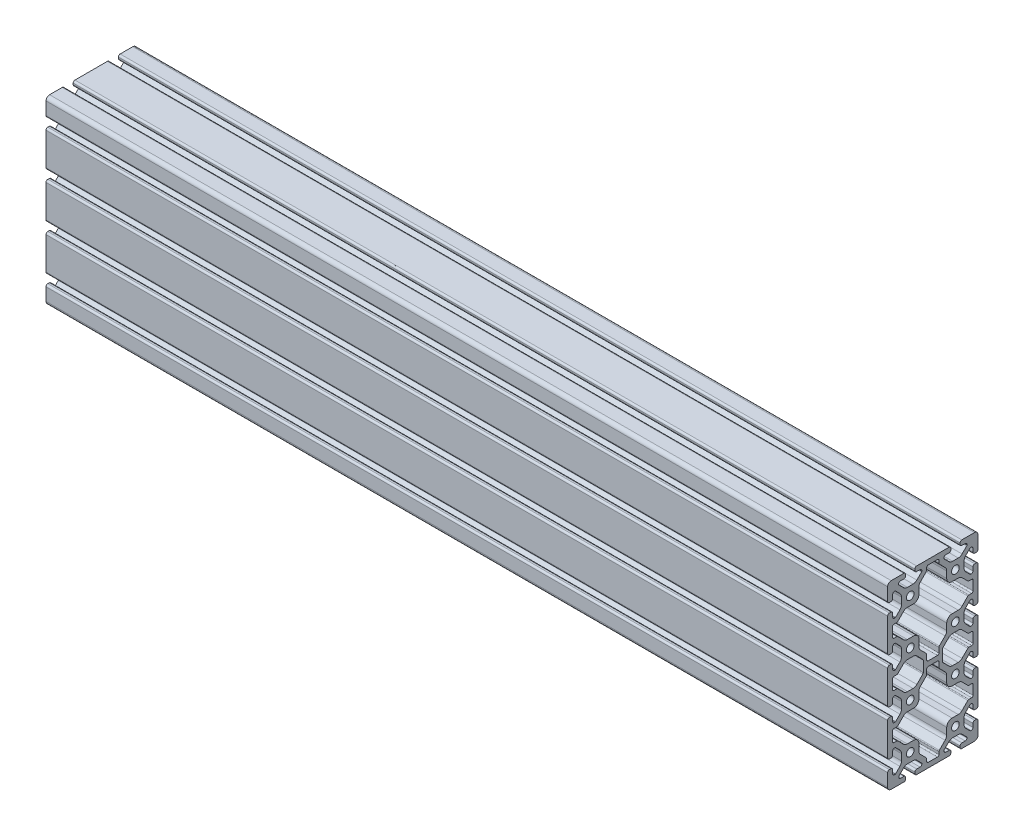
SolidWorks part; units mm, degrees
ref_plane "Front Plane" through (0, 0, 0) normal (0, 0, 1) x (1, 0, 0)
ref_plane "Top Plane" through (0, 0, 0) normal (0, 1, 0) x (1, 0, 0)
ref_plane "Right Plane" through (0, 0, 0) normal (1, 0, 0) x (0, 0, -1)
sketch "Sketch1" plane through (0, 0, 0) normal (0, 1, 0) x (1, 0, 0)
  line L0 (0, 0) -> (745, 0)
  dimension "D1" = 745
other "Aluminum 80X160(1)"
ref_plane "Plane1" through (0, 0, 0) normal (1, 0, 0) x (0, 0, -1)
sketch "Sketch13" plane through (0, 0, 0) normal (1, 0, 0) x (0, 0, -1)
  line L0 (-24.13, 57.84) -> (-15.87, 57.84)
  line L1 (-14.6, 56.57) -> (-14.6, 52.2333)
  line L2 (-14.228, 51.3353) -> (-9.1098, 46.2171)
  line L3 (-7.685, 42.7773) -> (-7.685, 37.065)
  line L4 (-2.935, 32.315) -> (2.5008, 32.315)
  line L5 (5.8595, 30.9238) -> (11.0113, 25.772)
  line L6 (11.9093, 25.4) -> (14.41, 25.4)
  line L7 (15.68, 24.13) -> (15.68, 15.87)
  line L8 (14.41, 14.6) -> (11.9093, 14.6)
  line L9 (11.0113, 14.228) -> (5.8595, 9.0762)
  line L10 (2.5008, 7.685) -> (-2.935, 7.685)
  line L11 (-7.685, 2.935) -> (-7.685, -2.7773)
  line L12 (-9.1098, -6.2171) -> (-14.228, -11.3353)
  line L13 (-14.6, -12.2334) -> (-14.6, -14.41)
  line L14 (-15.87, -15.68) -> (-24.13, -15.68)
  line L15 (-25.4, -14.41) -> (-25.4, -12.2334)
  line L16 (-25.772, -11.3353) -> (-30.8902, -6.2171)
  line L17 (-32.315, -2.7773) -> (-32.315, 2.935)
  line L18 (-37.065, 7.685) -> (-42.5008, 7.685)
  line L19 (-45.8595, 9.0762) -> (-51.0113, 14.228)
  line L20 (-51.9093, 14.6) -> (-54.41, 14.6)
  line L21 (-55.68, 15.87) -> (-55.68, 24.13)
  line L22 (-54.41, 25.4) -> (-51.9093, 25.4)
  line L23 (-51.0113, 25.772) -> (-45.8595, 30.9238)
  line L24 (-42.5008, 32.315) -> (-37.065, 32.315)
  line L25 (-32.315, 37.065) -> (-32.315, 42.7773)
  line L26 (-30.8902, 46.2171) -> (-25.772, 51.3353)
  line L27 (-25.4, 52.2333) -> (-25.4, 56.57)
  line L28 (-28.802, 54.4147) -> (-34.1405, 49.0762)
  line L29 (-37.4992, 47.685) -> (-42.5008, 47.685)
  line L30 (-45.8595, 49.0762) -> (-51.0113, 54.228)
  line L31 (-51.9093, 54.6) -> (-54.41, 54.6)
  line L32 (-55.68, 55.87) -> (-55.68, 64.13)
  line L33 (-54.41, 65.4) -> (-51.9093, 65.4)
  line L34 (-51.0113, 65.772) -> (-45.8595, 70.9238)
  line L35 (-42.5008, 72.315) -> (-37.4992, 72.315)
  line L36 (-34.1405, 70.9238) -> (-28.802, 65.5853)
  line L37 (-28.43, 64.6872) -> (-28.43, 55.3128)
  line L38 (-11.57, 55.3128) -> (-11.57, 64.6872)
  line L39 (-11.198, 65.5853) -> (-5.8595, 70.9238)
  line L40 (-2.5008, 72.315) -> (2.5008, 72.315)
  line L41 (5.8595, 70.9238) -> (11.0113, 65.772)
  line L42 (11.9093, 65.4) -> (14.41, 65.4)
  line L43 (15.68, 64.13) -> (15.68, 55.87)
  line L44 (14.41, 54.6) -> (11.9093, 54.6)
  line L45 (11.0113, 54.228) -> (5.8595, 49.0762)
  line L46 (2.5008, 47.685) -> (-2.5008, 47.685)
  line L47 (-5.8595, 49.0762) -> (-11.198, 54.4147)
  line L48 (-15.87, 62.16) -> (-24.13, 62.16)
  line L49 (-25.4, 63.43) -> (-25.4, 67.7667)
  line L50 (-25.772, 68.6647) -> (-30.8902, 73.7829)
  line L51 (-32.315, 77.2227) -> (-32.315, 82.935)
  line L52 (-37.065, 87.685) -> (-42.5008, 87.685)
  line L53 (-45.8595, 89.0762) -> (-51.0113, 94.228)
  line L54 (-51.9093, 94.6) -> (-54.41, 94.6)
  line L55 (-55.68, 95.87) -> (-55.68, 104.13)
  line L56 (-54.41, 105.4) -> (-51.9093, 105.4)
  line L57 (-51.0113, 105.772) -> (-45.8595, 110.9238)
  line L58 (-42.5008, 112.315) -> (-37.065, 112.315)
  line L59 (-32.315, 117.065) -> (-32.315, 122.7773)
  line L60 (-30.8902, 126.2171) -> (-25.772, 131.3353)
  line L61 (-25.4, 132.2334) -> (-25.4, 134.41)
  line L62 (-24.13, 135.68) -> (-15.87, 135.68)
  line L63 (-14.6, 134.41) -> (-14.6, 132.2334)
  line L64 (-14.228, 131.3353) -> (-9.1098, 126.2171)
  line L65 (-7.685, 122.7773) -> (-7.685, 117.065)
  line L66 (-2.935, 112.315) -> (2.5008, 112.315)
  line L67 (5.8595, 110.9238) -> (11.0113, 105.772)
  line L68 (11.9093, 105.4) -> (14.41, 105.4)
  line L69 (15.68, 104.13) -> (15.68, 95.87)
  line L70 (14.41, 94.6) -> (11.9093, 94.6)
  line L71 (11.0113, 94.228) -> (5.8595, 89.0762)
  line L72 (2.5008, 87.685) -> (-2.935, 87.685)
  line L73 (-7.685, 82.935) -> (-7.685, 77.2227)
  line L74 (-9.1098, 73.7829) -> (-14.228, 68.6647)
  line L75 (-14.6, 67.7667) -> (-14.6, 63.43)
  line L76 (18.43, 115.94) -> (17.0946, 115.94)
  line L77 (15.5246, 114.37) -> (15.5246, 111.285)
  line L78 (13.9546, 109.715) -> (13.4925, 109.715)
  line L79 (12.9551, 109.9376) -> (9.1098, 113.7829)
  line L80 (7.685, 117.2227) -> (7.685, 122.7773)
  line L81 (9.1098, 126.2171) -> (12.9551, 130.0624)
  line L82 (13.4925, 130.285) -> (13.9546, 130.285)
  line L83 (15.5246, 128.715) -> (15.5246, 125.63)
  line L84 (17.0946, 124.06) -> (18.43, 124.06)
  line L85 (20, 125.63) -> (20, 136.83)
  line L86 (16.83, 140) -> (5.63, 140)
  line L87 (4.06, 138.43) -> (4.06, 137.25)
  line L88 (5.63, 135.68) -> (8.7154, 135.68)
  line L89 (10.2854, 134.11) -> (10.2854, 133.6201)
  line L90 (9.947, 133.1637) -> (5.8595, 129.0762)
  line L91 (2.5008, 127.685) -> (-2.5008, 127.685)
  line L92 (-5.8595, 129.0762) -> (-10.0628, 133.2795)
  line L93 (-10.2854, 133.8169) -> (-10.2854, 134.11)
  line L94 (-8.7154, 135.68) -> (-5.63, 135.68)
  line L95 (-4.06, 137.25) -> (-4.06, 138.43)
  line L96 (-5.63, 140) -> (-34.37, 140)
  line L97 (-35.94, 138.43) -> (-35.94, 137.25)
  line L98 (-34.37, 135.68) -> (-31.2846, 135.68)
  line L99 (-29.7146, 134.11) -> (-29.7146, 133.6201)
  line L100 (-30.053, 133.1637) -> (-34.1405, 129.0762)
  line L101 (-37.4992, 127.685) -> (-42.5008, 127.685)
  line L102 (-45.8595, 129.0762) -> (-50.0628, 133.2795)
  line L103 (-50.2854, 133.8169) -> (-50.2854, 134.11)
  line L104 (-48.7154, 135.68) -> (-45.63, 135.68)
  line L105 (-44.06, 137.25) -> (-44.06, 138.43)
  line L106 (-45.63, 140) -> (-56.83, 140)
  line L107 (-60, 136.83) -> (-60, 125.63)
  line L108 (-58.43, 124.06) -> (-57.0946, 124.06)
  line L109 (-55.5246, 125.63) -> (-55.5246, 128.715)
  line L110 (-53.9546, 130.285) -> (-53.4925, 130.285)
  line L111 (-52.9551, 130.0624) -> (-49.1098, 126.2171)
  line L112 (-47.685, 122.7773) -> (-47.685, 117.2227)
  line L113 (-49.1098, 113.7829) -> (-52.9551, 109.9376)
  line L114 (-53.4925, 109.715) -> (-53.9546, 109.715)
  line L115 (-55.5246, 111.285) -> (-55.5246, 114.37)
  line L116 (-57.0946, 115.94) -> (-58.43, 115.94)
  line L117 (-60, 114.37) -> (-60, 85.63)
  line L118 (-58.43, 84.06) -> (-57.0946, 84.06)
  line L119 (-55.5246, 85.63) -> (-55.5246, 88.715)
  line L120 (-53.9546, 90.285) -> (-53.4925, 90.285)
  line L121 (-52.9551, 90.0624) -> (-49.1098, 86.2171)
  line L122 (-47.685, 82.7773) -> (-47.685, 77.2227)
  line L123 (-49.1098, 73.7829) -> (-52.9551, 69.9376)
  line L124 (-53.4925, 69.715) -> (-53.9546, 69.715)
  line L125 (-55.5246, 71.285) -> (-55.5246, 74.37)
  line L126 (-57.0946, 75.94) -> (-58.43, 75.94)
  line L127 (-60, 74.37) -> (-60, 45.63)
  line L128 (-58.43, 44.06) -> (-57.0946, 44.06)
  line L129 (-55.5246, 45.63) -> (-55.5246, 48.715)
  line L130 (-53.9546, 50.285) -> (-53.4925, 50.285)
  line L131 (-52.9551, 50.0624) -> (-49.1098, 46.2171)
  line L132 (-47.685, 42.7773) -> (-47.685, 37.2227)
  line L133 (-49.1098, 33.7829) -> (-52.9551, 29.9376)
  line L134 (-53.4925, 29.715) -> (-53.9546, 29.715)
  line L135 (-55.5246, 31.285) -> (-55.5246, 34.37)
  line L136 (-57.0946, 35.94) -> (-58.43, 35.94)
  line L137 (-60, 34.37) -> (-60, 5.63)
  line L138 (-58.43, 4.06) -> (-57.0946, 4.06)
  line L139 (-55.5246, 5.63) -> (-55.5246, 8.715)
  line L140 (-53.9546, 10.285) -> (-53.4925, 10.285)
  line L141 (-52.9551, 10.0624) -> (-49.1098, 6.2171)
  line L142 (-47.685, 2.7773) -> (-47.685, -2.7773)
  line L143 (-49.1098, -6.2171) -> (-52.9551, -10.0624)
  line L144 (-53.4925, -10.285) -> (-53.9546, -10.285)
  line L145 (-55.5246, -8.715) -> (-55.5246, -5.63)
  line L146 (-57.0946, -4.06) -> (-58.43, -4.06)
  line L147 (-60, -5.63) -> (-60, -16.83)
  line L148 (-56.83, -20) -> (-45.573, -20)
  line L149 (-44.003, -18.43) -> (-44.003, -17.25)
  line L150 (-45.573, -15.68) -> (-48.4757, -15.68)
  line L151 (-50.0447, -14.0552) -> (-50.033, -13.7199)
  line L152 (-49.8238, -13.0405) -> (-45.8595, -9.0762)
  line L153 (-42.5008, -7.685) -> (-37.4992, -7.685)
  line L154 (-34.1405, -9.0762) -> (-29.9372, -13.2795)
  line L155 (-29.7146, -13.8169) -> (-29.7146, -14.11)
  line L156 (-31.2846, -15.68) -> (-34.2421, -15.68)
  line L157 (-35.8795, -17.25) -> (-35.8795, -18.43)
  line L158 (-34.2421, -20) -> (-5.573, -20)
  line L159 (-4.003, -18.43) -> (-4.003, -17.25)
  line L160 (-5.573, -15.68) -> (-8.4757, -15.68)
  line L161 (-10.0447, -14.0552) -> (-10.033, -13.7199)
  line L162 (-9.8238, -13.0405) -> (-5.8595, -9.0762)
  line L163 (-2.5008, -7.685) -> (2.5008, -7.685)
  line L164 (5.8595, -9.0762) -> (10.0628, -13.2795)
  line L165 (10.2854, -13.8169) -> (10.2854, -14.11)
  line L166 (8.7154, -15.68) -> (5.7579, -15.68)
  line L167 (4.1204, -17.2515) -> (4.1204, -18.4315)
  line L168 (5.7579, -20) -> (17.0184, -20)
  line L169 (20, -16.6746) -> (20, -5.63)
  line L170 (18.43, -4.06) -> (17.0946, -4.06)
  line L171 (15.5246, -5.63) -> (15.5246, -8.715)
  line L172 (13.9546, -10.285) -> (13.4925, -10.285)
  line L173 (12.9551, -10.0624) -> (9.1098, -6.2171)
  line L174 (7.685, -2.7773) -> (7.685, 2.7773)
  line L175 (9.1098, 6.2171) -> (12.9551, 10.0624)
  line L176 (13.4925, 10.285) -> (13.9546, 10.285)
  line L177 (15.5246, 8.715) -> (15.5246, 5.63)
  line L178 (17.0946, 4.06) -> (18.43, 4.06)
  line L179 (20, 5.63) -> (20, 34.37)
  line L180 (18.43, 35.94) -> (17.0946, 35.94)
  line L181 (15.5246, 34.37) -> (15.5246, 31.285)
  line L182 (13.9546, 29.715) -> (13.4925, 29.715)
  line L183 (12.9551, 29.9376) -> (9.1098, 33.7829)
  line L184 (7.685, 37.2227) -> (7.685, 42.7773)
  line L185 (9.1098, 46.2171) -> (12.9551, 50.0624)
  line L186 (13.4925, 50.285) -> (13.9546, 50.285)
  line L187 (15.5246, 48.715) -> (15.5246, 45.63)
  line L188 (17.0946, 44.06) -> (18.43, 44.06)
  line L189 (20, 45.63) -> (20, 74.37)
  line L190 (18.43, 75.94) -> (17.0946, 75.94)
  line L191 (15.5246, 74.37) -> (15.5246, 71.285)
  line L192 (13.9546, 69.715) -> (13.4925, 69.715)
  line L193 (12.9551, 69.9376) -> (9.1098, 73.7829)
  line L194 (7.685, 77.2227) -> (7.685, 82.7773)
  line L195 (9.1098, 86.2171) -> (12.9551, 90.0624)
  line L196 (13.4925, 90.285) -> (13.9546, 90.285)
  line L197 (15.5246, 88.715) -> (15.5246, 85.63)
  line L198 (17.0946, 84.06) -> (18.43, 84.06)
  line L199 (20, 85.63) -> (20, 114.37)
  arc A0 (-14.6, 56.57) -> (-15.87, 57.84) centre (-15.87, 56.57) ccw
  arc A1 (-14.6, 52.2333) -> (-14.228, 51.3353) centre (-13.33, 52.2333) ccw
  arc A2 (-7.685, 42.7773) -> (-9.1098, 46.2171) centre (-12.5496, 42.7773) ccw
  arc A3 (-7.685, 37.065) -> (-2.935, 32.315) centre (-2.935, 37.065) ccw
  arc A4 (5.8595, 30.9238) -> (2.5008, 32.315) centre (2.5008, 27.565) ccw
  arc A5 (11.0113, 25.772) -> (11.9093, 25.4) centre (11.9093, 26.67) ccw
  arc A6 (15.68, 24.13) -> (14.41, 25.4) centre (14.41, 24.13) ccw
  arc A7 (14.41, 14.6) -> (15.68, 15.87) centre (14.41, 15.87) ccw
  arc A8 (11.9093, 14.6) -> (11.0113, 14.228) centre (11.9093, 13.33) ccw
  arc A9 (2.5008, 7.685) -> (5.8595, 9.0762) centre (2.5008, 12.435) ccw
  arc A10 (-2.935, 7.685) -> (-7.685, 2.935) centre (-2.935, 2.935) ccw
  arc A11 (-9.1098, -6.2171) -> (-7.685, -2.7773) centre (-12.5496, -2.7773) ccw
  arc A12 (-14.228, -11.3353) -> (-14.6, -12.2334) centre (-13.33, -12.2334) ccw
  arc A13 (-15.87, -15.68) -> (-14.6, -14.41) centre (-15.87, -14.41) ccw
  arc A14 (-25.4, -14.41) -> (-24.13, -15.68) centre (-24.13, -14.41) ccw
  arc A15 (-25.4, -12.2334) -> (-25.772, -11.3353) centre (-26.67, -12.2334) ccw
  arc A16 (-32.315, -2.7773) -> (-30.8902, -6.2171) centre (-27.4504, -2.7773) ccw
  arc A17 (-32.315, 2.935) -> (-37.065, 7.685) centre (-37.065, 2.935) ccw
  arc A18 (-45.8595, 9.0762) -> (-42.5008, 7.685) centre (-42.5008, 12.435) ccw
  arc A19 (-51.0113, 14.228) -> (-51.9093, 14.6) centre (-51.9093, 13.33) ccw
  arc A20 (-55.68, 15.87) -> (-54.41, 14.6) centre (-54.41, 15.87) ccw
  arc A21 (-54.41, 25.4) -> (-55.68, 24.13) centre (-54.41, 24.13) ccw
  arc A22 (-51.9093, 25.4) -> (-51.0113, 25.772) centre (-51.9093, 26.67) ccw
  arc A23 (-42.5008, 32.315) -> (-45.8595, 30.9238) centre (-42.5008, 27.565) ccw
  arc A24 (-37.065, 32.315) -> (-32.315, 37.065) centre (-37.065, 37.065) ccw
  arc A25 (-30.8902, 46.2171) -> (-32.315, 42.7773) centre (-27.4504, 42.7773) ccw
  arc A26 (-25.772, 51.3353) -> (-25.4, 52.2333) centre (-26.67, 52.2333) ccw
  arc A27 (-24.13, 57.84) -> (-25.4, 56.57) centre (-24.13, 56.57) ccw
  arc A28 (-28.802, 54.4147) -> (-28.43, 55.3128) centre (-29.7, 55.3128) ccw
  arc A29 (-37.4992, 47.685) -> (-34.1405, 49.0762) centre (-37.4992, 52.435) ccw
  arc A30 (-45.8595, 49.0762) -> (-42.5008, 47.685) centre (-42.5008, 52.435) ccw
  arc A31 (-51.0113, 54.228) -> (-51.9093, 54.6) centre (-51.9093, 53.33) ccw
  arc A32 (-55.68, 55.87) -> (-54.41, 54.6) centre (-54.41, 55.87) ccw
  arc A33 (-54.41, 65.4) -> (-55.68, 64.13) centre (-54.41, 64.13) ccw
  arc A34 (-51.9093, 65.4) -> (-51.0113, 65.772) centre (-51.9093, 66.67) ccw
  arc A35 (-42.5008, 72.315) -> (-45.8595, 70.9238) centre (-42.5008, 67.565) ccw
  arc A36 (-34.1405, 70.9238) -> (-37.4992, 72.315) centre (-37.4992, 67.565) ccw
  arc A37 (-28.43, 64.6872) -> (-28.802, 65.5853) centre (-29.7, 64.6872) ccw
  circle A38 centre (-40, 40) radius 3.4
  circle A39 centre (0, 40) radius 3.4
  circle A40 centre (-40, 120) radius 3.4
  circle A41 centre (0, 120) radius 3.4
  circle A42 centre (0, 80) radius 3.4
  circle A43 centre (-40, 80) radius 3.4
  circle A44 centre (0, 0) radius 3.4
  circle A45 centre (-40, 0) radius 3.4
  arc A46 (-11.198, 65.5853) -> (-11.57, 64.6872) centre (-10.3, 64.6872) ccw
  arc A47 (-2.5008, 72.315) -> (-5.8595, 70.9238) centre (-2.5008, 67.565) ccw
  arc A48 (5.8595, 70.9238) -> (2.5008, 72.315) centre (2.5008, 67.565) ccw
  arc A49 (11.0113, 65.772) -> (11.9093, 65.4) centre (11.9093, 66.67) ccw
  arc A50 (15.68, 64.13) -> (14.41, 65.4) centre (14.41, 64.13) ccw
  arc A51 (14.41, 54.6) -> (15.68, 55.87) centre (14.41, 55.87) ccw
  arc A52 (11.9093, 54.6) -> (11.0113, 54.228) centre (11.9093, 53.33) ccw
  arc A53 (2.5008, 47.685) -> (5.8595, 49.0762) centre (2.5008, 52.435) ccw
  arc A54 (-5.8595, 49.0762) -> (-2.5008, 47.685) centre (-2.5008, 52.435) ccw
  arc A55 (-11.57, 55.3128) -> (-11.198, 54.4147) centre (-10.3, 55.3128) ccw
  arc A56 (-15.87, 62.16) -> (-14.6, 63.43) centre (-15.87, 63.43) ccw
  arc A57 (-25.4, 63.43) -> (-24.13, 62.16) centre (-24.13, 63.43) ccw
  arc A58 (-25.4, 67.7667) -> (-25.772, 68.6647) centre (-26.67, 67.7667) ccw
  arc A59 (-32.315, 77.2227) -> (-30.8902, 73.7829) centre (-27.4504, 77.2227) ccw
  arc A60 (-32.315, 82.935) -> (-37.065, 87.685) centre (-37.065, 82.935) ccw
  arc A61 (-45.8595, 89.0762) -> (-42.5008, 87.685) centre (-42.5008, 92.435) ccw
  arc A62 (-51.0113, 94.228) -> (-51.9093, 94.6) centre (-51.9093, 93.33) ccw
  arc A63 (-55.68, 95.87) -> (-54.41, 94.6) centre (-54.41, 95.87) ccw
  arc A64 (-54.41, 105.4) -> (-55.68, 104.13) centre (-54.41, 104.13) ccw
  arc A65 (-51.9093, 105.4) -> (-51.0113, 105.772) centre (-51.9093, 106.67) ccw
  arc A66 (-42.5008, 112.315) -> (-45.8595, 110.9238) centre (-42.5008, 107.565) ccw
  arc A67 (-37.065, 112.315) -> (-32.315, 117.065) centre (-37.065, 117.065) ccw
  arc A68 (-30.8902, 126.2171) -> (-32.315, 122.7773) centre (-27.4504, 122.7773) ccw
  arc A69 (-25.772, 131.3353) -> (-25.4, 132.2334) centre (-26.67, 132.2334) ccw
  arc A70 (-24.13, 135.68) -> (-25.4, 134.41) centre (-24.13, 134.41) ccw
  arc A71 (-14.6, 134.41) -> (-15.87, 135.68) centre (-15.87, 134.41) ccw
  arc A72 (-14.6, 132.2334) -> (-14.228, 131.3353) centre (-13.33, 132.2334) ccw
  arc A73 (-7.685, 122.7773) -> (-9.1098, 126.2171) centre (-12.5496, 122.7773) ccw
  arc A74 (-7.685, 117.065) -> (-2.935, 112.315) centre (-2.935, 117.065) ccw
  arc A75 (5.8595, 110.9238) -> (2.5008, 112.315) centre (2.5008, 107.565) ccw
  arc A76 (11.0113, 105.772) -> (11.9093, 105.4) centre (11.9093, 106.67) ccw
  arc A77 (15.68, 104.13) -> (14.41, 105.4) centre (14.41, 104.13) ccw
  arc A78 (14.41, 94.6) -> (15.68, 95.87) centre (14.41, 95.87) ccw
  arc A79 (11.9093, 94.6) -> (11.0113, 94.228) centre (11.9093, 93.33) ccw
  arc A80 (2.5008, 87.685) -> (5.8595, 89.0762) centre (2.5008, 92.435) ccw
  arc A81 (-2.935, 87.685) -> (-7.685, 82.935) centre (-2.935, 82.935) ccw
  arc A82 (-9.1098, 73.7829) -> (-7.685, 77.2227) centre (-12.5496, 77.2227) ccw
  arc A83 (-14.228, 68.6647) -> (-14.6, 67.7667) centre (-13.33, 67.7667) ccw
  arc A84 (17.0946, 115.94) -> (15.5246, 114.37) centre (17.0946, 114.37) ccw
  arc A85 (13.9546, 109.715) -> (15.5246, 111.285) centre (13.9546, 111.285) ccw
  arc A86 (12.9551, 109.9376) -> (13.4925, 109.715) centre (13.4925, 110.475) ccw
  arc A87 (7.685, 117.2227) -> (9.1098, 113.7829) centre (12.5496, 117.2227) ccw
  arc A88 (9.1098, 126.2171) -> (7.685, 122.7773) centre (12.5496, 122.7773) ccw
  arc A89 (13.4925, 130.285) -> (12.9551, 130.0624) centre (13.4925, 129.525) ccw
  arc A90 (15.5246, 128.715) -> (13.9546, 130.285) centre (13.9546, 128.715) ccw
  arc A91 (15.5246, 125.63) -> (17.0946, 124.06) centre (17.0946, 125.63) ccw
  arc A92 (18.43, 124.06) -> (20, 125.63) centre (18.43, 125.63) ccw
  arc A93 (20, 136.83) -> (16.83, 140) centre (16.83, 136.83) ccw
  arc A94 (5.63, 140) -> (4.06, 138.43) centre (5.63, 138.43) ccw
  arc A95 (4.06, 137.25) -> (5.63, 135.68) centre (5.63, 137.25) ccw
  arc A96 (10.2854, 134.11) -> (8.7154, 135.68) centre (8.7154, 134.11) ccw
  arc A97 (9.947, 133.1637) -> (10.2854, 133.6201) centre (9.55, 133.8117) ccw
  arc A98 (2.5008, 127.685) -> (5.8595, 129.0762) centre (2.5008, 132.435) ccw
  arc A99 (-5.8595, 129.0762) -> (-2.5008, 127.685) centre (-2.5008, 132.435) ccw
  arc A100 (-10.2854, 133.8169) -> (-10.0628, 133.2795) centre (-9.5254, 133.8169) ccw
  arc A101 (-8.7154, 135.68) -> (-10.2854, 134.11) centre (-8.7154, 134.11) ccw
  arc A102 (-5.63, 135.68) -> (-4.06, 137.25) centre (-5.63, 137.25) ccw
  arc A103 (-4.06, 138.43) -> (-5.63, 140) centre (-5.63, 138.43) ccw
  arc A104 (-34.37, 140) -> (-35.94, 138.43) centre (-34.37, 138.43) ccw
  arc A105 (-35.94, 137.25) -> (-34.37, 135.68) centre (-34.37, 137.25) ccw
  arc A106 (-29.7146, 134.11) -> (-31.2846, 135.68) centre (-31.2846, 134.11) ccw
  arc A107 (-30.053, 133.1637) -> (-29.7146, 133.6201) centre (-30.45, 133.8117) ccw
  arc A108 (-37.4992, 127.685) -> (-34.1405, 129.0762) centre (-37.4992, 132.435) ccw
  arc A109 (-45.8595, 129.0762) -> (-42.5008, 127.685) centre (-42.5008, 132.435) ccw
  arc A110 (-50.2854, 133.8169) -> (-50.0628, 133.2795) centre (-49.5254, 133.8169) ccw
  arc A111 (-48.7154, 135.68) -> (-50.2854, 134.11) centre (-48.7154, 134.11) ccw
  arc A112 (-45.63, 135.68) -> (-44.06, 137.25) centre (-45.63, 137.25) ccw
  arc A113 (-44.06, 138.43) -> (-45.63, 140) centre (-45.63, 138.43) ccw
  arc A114 (-56.83, 140) -> (-60, 136.83) centre (-56.83, 136.83) ccw
  arc A115 (-60, 125.63) -> (-58.43, 124.06) centre (-58.43, 125.63) ccw
  arc A116 (-57.0946, 124.06) -> (-55.5246, 125.63) centre (-57.0946, 125.63) ccw
  arc A117 (-53.9546, 130.285) -> (-55.5246, 128.715) centre (-53.9546, 128.715) ccw
  arc A118 (-52.9551, 130.0624) -> (-53.4925, 130.285) centre (-53.4925, 129.525) ccw
  arc A119 (-47.685, 122.7773) -> (-49.1098, 126.2171) centre (-52.5496, 122.7773) ccw
  arc A120 (-49.1098, 113.7829) -> (-47.685, 117.2227) centre (-52.5496, 117.2227) ccw
  arc A121 (-53.4925, 109.715) -> (-52.9551, 109.9376) centre (-53.4925, 110.475) ccw
  arc A122 (-55.5246, 111.285) -> (-53.9546, 109.715) centre (-53.9546, 111.285) ccw
  arc A123 (-55.5246, 114.37) -> (-57.0946, 115.94) centre (-57.0946, 114.37) ccw
  arc A124 (-58.43, 115.94) -> (-60, 114.37) centre (-58.43, 114.37) ccw
  arc A125 (-60, 85.63) -> (-58.43, 84.06) centre (-58.43, 85.63) ccw
  arc A126 (-57.0946, 84.06) -> (-55.5246, 85.63) centre (-57.0946, 85.63) ccw
  arc A127 (-53.9546, 90.285) -> (-55.5246, 88.715) centre (-53.9546, 88.715) ccw
  arc A128 (-52.9551, 90.0624) -> (-53.4925, 90.285) centre (-53.4925, 89.525) ccw
  arc A129 (-47.685, 82.7773) -> (-49.1098, 86.2171) centre (-52.5496, 82.7773) ccw
  arc A130 (-49.1098, 73.7829) -> (-47.685, 77.2227) centre (-52.5496, 77.2227) ccw
  arc A131 (-53.4925, 69.715) -> (-52.9551, 69.9376) centre (-53.4925, 70.475) ccw
  arc A132 (-55.5246, 71.285) -> (-53.9546, 69.715) centre (-53.9546, 71.285) ccw
  arc A133 (-55.5246, 74.37) -> (-57.0946, 75.94) centre (-57.0946, 74.37) ccw
  arc A134 (-58.43, 75.94) -> (-60, 74.37) centre (-58.43, 74.37) ccw
  arc A135 (-60, 45.63) -> (-58.43, 44.06) centre (-58.43, 45.63) ccw
  arc A136 (-57.0946, 44.06) -> (-55.5246, 45.63) centre (-57.0946, 45.63) ccw
  arc A137 (-53.9546, 50.285) -> (-55.5246, 48.715) centre (-53.9546, 48.715) ccw
  arc A138 (-52.9551, 50.0624) -> (-53.4925, 50.285) centre (-53.4925, 49.525) ccw
  arc A139 (-47.685, 42.7773) -> (-49.1098, 46.2171) centre (-52.5496, 42.7773) ccw
  arc A140 (-49.1098, 33.7829) -> (-47.685, 37.2227) centre (-52.5496, 37.2227) ccw
  arc A141 (-53.4925, 29.715) -> (-52.9551, 29.9376) centre (-53.4925, 30.475) ccw
  arc A142 (-55.5246, 31.285) -> (-53.9546, 29.715) centre (-53.9546, 31.285) ccw
  arc A143 (-55.5246, 34.37) -> (-57.0946, 35.94) centre (-57.0946, 34.37) ccw
  arc A144 (-58.43, 35.94) -> (-60, 34.37) centre (-58.43, 34.37) ccw
  arc A145 (-60, 5.63) -> (-58.43, 4.06) centre (-58.43, 5.63) ccw
  arc A146 (-57.0946, 4.06) -> (-55.5246, 5.63) centre (-57.0946, 5.63) ccw
  arc A147 (-53.9546, 10.285) -> (-55.5246, 8.715) centre (-53.9546, 8.715) ccw
  arc A148 (-52.9551, 10.0624) -> (-53.4925, 10.285) centre (-53.4925, 9.525) ccw
  arc A149 (-47.685, 2.7773) -> (-49.1098, 6.2171) centre (-52.5496, 2.7773) ccw
  arc A150 (-49.1098, -6.2171) -> (-47.685, -2.7773) centre (-52.5496, -2.7773) ccw
  arc A151 (-53.4925, -10.285) -> (-52.9551, -10.0624) centre (-53.4925, -9.525) ccw
  arc A152 (-55.5246, -8.715) -> (-53.9546, -10.285) centre (-53.9546, -8.715) ccw
  arc A153 (-55.5246, -5.63) -> (-57.0946, -4.06) centre (-57.0946, -5.63) ccw
  arc A154 (-58.43, -4.06) -> (-60, -5.63) centre (-58.43, -5.63) ccw
  arc A155 (-60, -16.83) -> (-56.83, -20) centre (-56.83, -16.83) ccw
  arc A156 (-45.573, -20) -> (-44.003, -18.43) centre (-45.573, -18.43) ccw
  arc A157 (-44.003, -17.25) -> (-45.573, -15.68) centre (-45.573, -17.25) ccw
  arc A158 (-50.0447, -14.0552) -> (-48.4757, -15.68) centre (-48.4757, -14.11) ccw
  arc A159 (-49.8238, -13.0405) -> (-50.033, -13.7199) centre (-49.2864, -13.5779) ccw
  arc A160 (-42.5008, -7.685) -> (-45.8595, -9.0762) centre (-42.5008, -12.435) ccw
  arc A161 (-34.1405, -9.0762) -> (-37.4992, -7.685) centre (-37.4992, -12.435) ccw
  arc A162 (-29.7146, -13.8169) -> (-29.9372, -13.2795) centre (-30.4746, -13.8169) ccw
  arc A163 (-31.2846, -15.68) -> (-29.7146, -14.11) centre (-31.2846, -14.11) ccw
  arc A164 (-34.2421, -15.68) -> (-35.8795, -17.25) centre (-34.3096, -17.2485) ccw
  arc A165 (-35.8795, -18.43) -> (-34.2421, -20) centre (-34.3096, -18.4315) ccw
  arc A166 (-5.573, -20) -> (-4.003, -18.43) centre (-5.573, -18.43) ccw
  arc A167 (-4.003, -17.25) -> (-5.573, -15.68) centre (-5.573, -17.25) ccw
  arc A168 (-10.0447, -14.0552) -> (-8.4757, -15.68) centre (-8.4757, -14.11) ccw
  arc A169 (-9.8238, -13.0405) -> (-10.033, -13.7199) centre (-9.2864, -13.5779) ccw
  arc A170 (-2.5008, -7.685) -> (-5.8595, -9.0762) centre (-2.5008, -12.435) ccw
  arc A171 (5.8595, -9.0762) -> (2.5008, -7.685) centre (2.5008, -12.435) ccw
  arc A172 (10.2854, -13.8169) -> (10.0628, -13.2795) centre (9.5254, -13.8169) ccw
  arc A173 (8.7154, -15.68) -> (10.2854, -14.11) centre (8.7154, -14.11) ccw
  arc A174 (5.7579, -15.68) -> (4.1204, -17.2515) centre (5.6932, -17.2515) ccw
  arc A175 (4.1204, -18.4315) -> (5.7579, -20) centre (5.6904, -18.4315) ccw
  arc A176 (17.0184, -20) -> (20, -16.6746) centre (16.8341, -16.8354) ccw
  arc A177 (20, -5.63) -> (18.43, -4.06) centre (18.43, -5.63) ccw
  arc A178 (17.0946, -4.06) -> (15.5246, -5.63) centre (17.0946, -5.63) ccw
  arc A179 (13.9546, -10.285) -> (15.5246, -8.715) centre (13.9546, -8.715) ccw
  arc A180 (12.9551, -10.0624) -> (13.4925, -10.285) centre (13.4925, -9.525) ccw
  arc A181 (7.685, -2.7773) -> (9.1098, -6.2171) centre (12.5496, -2.7773) ccw
  arc A182 (9.1098, 6.2171) -> (7.685, 2.7773) centre (12.5496, 2.7773) ccw
  arc A183 (13.4925, 10.285) -> (12.9551, 10.0624) centre (13.4925, 9.525) ccw
  arc A184 (15.5246, 8.715) -> (13.9546, 10.285) centre (13.9546, 8.715) ccw
  arc A185 (15.5246, 5.63) -> (17.0946, 4.06) centre (17.0946, 5.63) ccw
  arc A186 (18.43, 4.06) -> (20, 5.63) centre (18.43, 5.63) ccw
  arc A187 (20, 34.37) -> (18.43, 35.94) centre (18.43, 34.37) ccw
  arc A188 (17.0946, 35.94) -> (15.5246, 34.37) centre (17.0946, 34.37) ccw
  arc A189 (13.9546, 29.715) -> (15.5246, 31.285) centre (13.9546, 31.285) ccw
  arc A190 (12.9551, 29.9376) -> (13.4925, 29.715) centre (13.4925, 30.475) ccw
  arc A191 (7.685, 37.2227) -> (9.1098, 33.7829) centre (12.5496, 37.2227) ccw
  arc A192 (9.1098, 46.2171) -> (7.685, 42.7773) centre (12.5496, 42.7773) ccw
  arc A193 (13.4925, 50.285) -> (12.9551, 50.0624) centre (13.4925, 49.525) ccw
  arc A194 (15.5246, 48.715) -> (13.9546, 50.285) centre (13.9546, 48.715) ccw
  arc A195 (15.5246, 45.63) -> (17.0946, 44.06) centre (17.0946, 45.63) ccw
  arc A196 (18.43, 44.06) -> (20, 45.63) centre (18.43, 45.63) ccw
  arc A197 (20, 74.37) -> (18.43, 75.94) centre (18.43, 74.37) ccw
  arc A198 (17.0946, 75.94) -> (15.5246, 74.37) centre (17.0946, 74.37) ccw
  arc A199 (13.9546, 69.715) -> (15.5246, 71.285) centre (13.9546, 71.285) ccw
  arc A200 (12.9551, 69.9376) -> (13.4925, 69.715) centre (13.4925, 70.475) ccw
  arc A201 (7.685, 77.2227) -> (9.1098, 73.7829) centre (12.5496, 77.2227) ccw
  arc A202 (9.1098, 86.2171) -> (7.685, 82.7773) centre (12.5496, 82.7773) ccw
  arc A203 (13.4925, 90.285) -> (12.9551, 90.0624) centre (13.4925, 89.525) ccw
  arc A204 (15.5246, 88.715) -> (13.9546, 90.285) centre (13.9546, 88.715) ccw
  arc A205 (15.5246, 85.63) -> (17.0946, 84.06) centre (17.0946, 85.63) ccw
  arc A206 (18.43, 84.06) -> (20, 85.63) centre (18.43, 85.63) ccw
  arc A207 (20, 114.37) -> (18.43, 115.94) centre (18.43, 114.37) ccw
  point P0 (0, 0)
  dimension "D1" = 6.8
  dimension "D2" = 40
  dimension "D3" = 40
  dimension "D4" = 80
  dimension "D5" = 120
